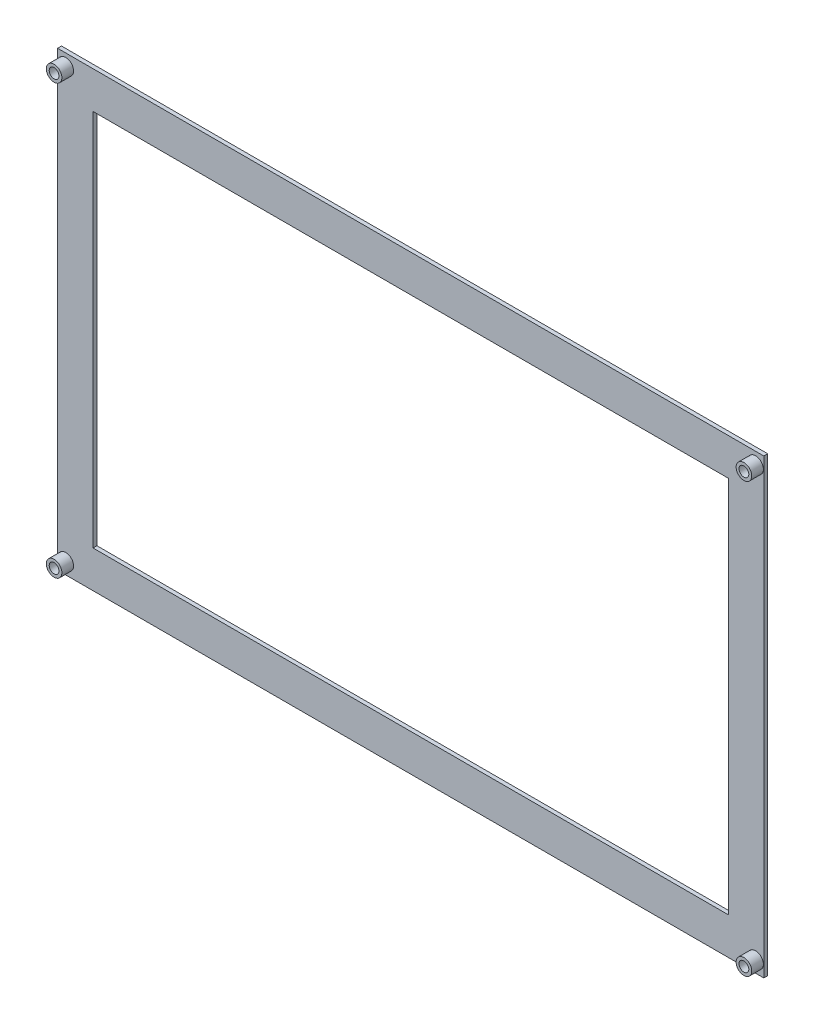
SolidWorks part; units mm, degrees
ref_plane "前视基准面" through (0, 0, 0) normal (0, 0, 1) x (1, 0, 0)
ref_plane "上视基准面" through (0, 0, 0) normal (0, 1, 0) x (1, 0, 0)
ref_plane "右视基准面" through (0, 0, 0) normal (1, 0, 0) x (0, 0, -1)
sketch "草图1" plane through (0, 0, 0) normal (0, 0, 1) x (1, 0, 0)
  line L1 (-90.6, 58) -> (90.6, 58)
  line L2 (-90.6, 58) -> (-90.6, -58)
  line L3 (-90.6, -58) -> (90.6, -58)
  line L4 (90.6, 58) -> (90.6, -58)
  line L5 (-90.6, 58) -> (90.6, -58) construction
  line L6 (-90.6, -58) -> (90.6, 58) construction
  point P0 (0, 0)
  dimension "D1" = 181.2
  dimension "D2" = 116
extrude "凸台-拉伸1" add sketch "草图1" along normal blind 1
sketch "草图2" plane through (0, 0, 1) normal (0, 0, 1) x (1, 0, 0)
  line L1 (-88.5, 55) -> (88.5, 55) construction
  line L2 (-88.5, 55) -> (-88.5, -55) construction
  line L3 (-88.5, -55) -> (88.5, -55) construction
  line L4 (88.5, 55) -> (88.5, -55) construction
  line L5 (-88.5, 55) -> (88.5, -55) construction
  line L6 (-88.5, -55) -> (88.5, 55) construction
  circle A0 centre (-88.5, 55) radius 2
  circle A1 centre (-88.5, 55) radius 1.25
  circle A2 centre (88.5, 55) radius 2
  circle A3 centre (88.5, 55) radius 1.25
  circle A4 centre (88.5, -55) radius 2
  circle A5 centre (88.5, -55) radius 1.25
  circle A6 centre (-88.5, -55) radius 2
  circle A7 centre (-88.5, -55) radius 1.25
  point P0 (0, 0)
  dimension "D3" = 4
  dimension "D4" = 2.5
  dimension "D1" = 177
  dimension "D2" = 110
extrude "凸台-拉伸2" add sketch "草图2" along normal blind 3
sketch "草图3" plane through (0, 0, 0) normal (0, 0, -1) x (-1, 0, 0)
  line L1 (-81.5, 48.5) -> (81.5, 48.5)
  line L2 (-81.5, 48.5) -> (-81.5, -48.5)
  line L3 (-81.5, -48.5) -> (81.5, -48.5)
  line L4 (81.5, 48.5) -> (81.5, -48.5)
  line L5 (-81.5, 48.5) -> (81.5, -48.5) construction
  line L6 (-81.5, -48.5) -> (81.5, 48.5) construction
  point P0 (0, 0)
  dimension "D1" = 163
  dimension "D2" = 97
extrude "切除-拉伸2" cut sketch "草图3" against normal blind 3
